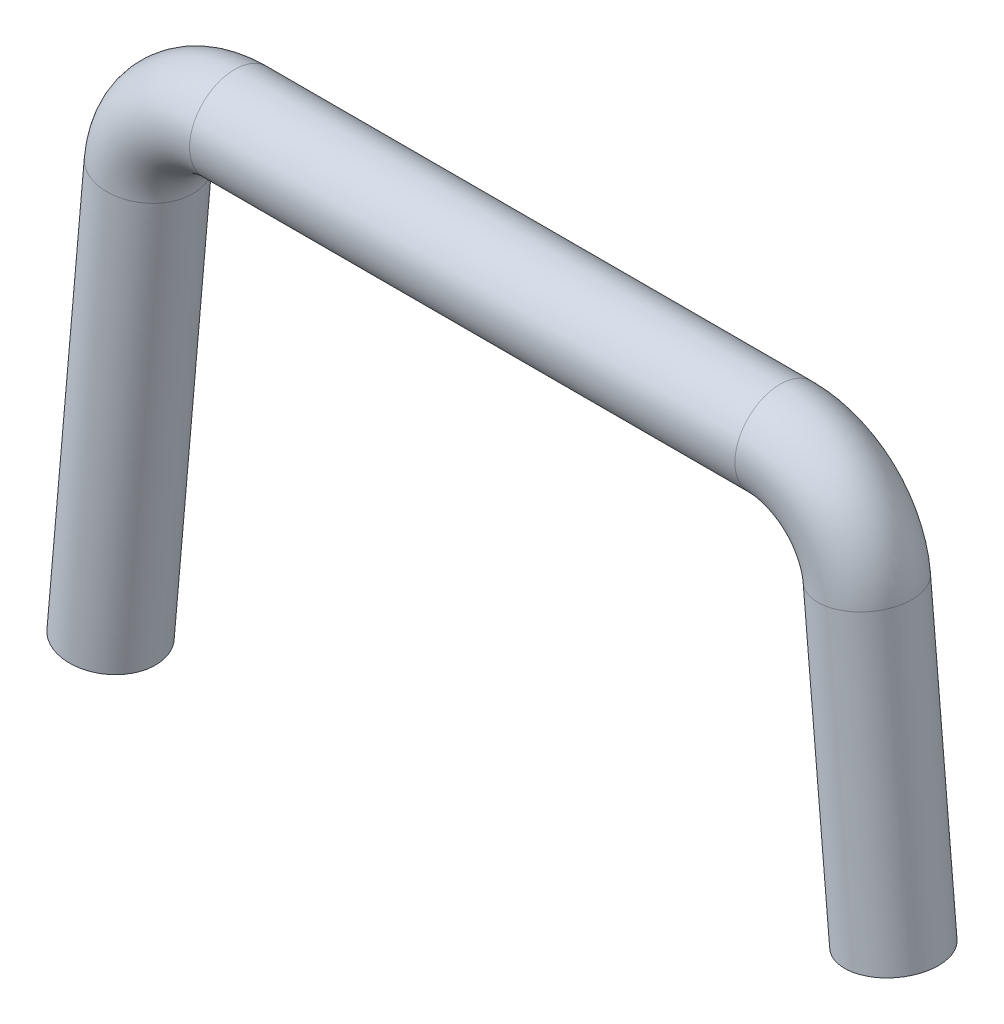
SolidWorks part; units mm, degrees
material "Alloy Steel"
ref_plane "Front Plane" through (0, 0, 0) normal (0, 0, 1) x (1, 0, 0)
ref_plane "Top Plane" through (0, 0, 0) normal (0, 1, 0) x (1, 0, 0)
ref_plane "Right Plane" through (0, 0, 0) normal (1, 0, 0) x (0, 0, -1)
sketch "Circle" plane through (0, 0, 0) normal (0, 0, 1) x (1, 0, 0)
  line L0 (0, 0) -> (5.7897, 66.1766)
  line L1 (19.2383, 78.5) -> (103.7827, 78.5)
  line L2 (117.2313, 66.1766) -> (121.35, 19.1)
  line L3 (0, 0) -> (0, 133.1903) construction
  arc A0 (5.7897, 66.1766) -> (19.2383, 78.5) centre (19.2383, 65) cw
  arc A1 (103.7827, 78.5) -> (117.2313, 66.1766) centre (103.7827, 65) cw
  dimension "D1" = 13.5
  dimension "D3" = 121.35
  dimension "D2" = 78.5
  dimension "D4" = 10
  dimension "D5" = 59.4
  dimension "D6" = 5
ref_plane "Plane1" through (0, 0, 0) normal (0.0872, 0.9962, 0) x (0.9962, -0.0872, 0)
sketch "Path" plane through (0, 0, 0) normal (0.0872, 0.9962, 0) x (0.9962, -0.0872, 0)
  circle A0 centre (0, 0) radius 7
  dimension "D1" = 14
sweep "Cam Handle" add profiles "Path" path "Circle"
